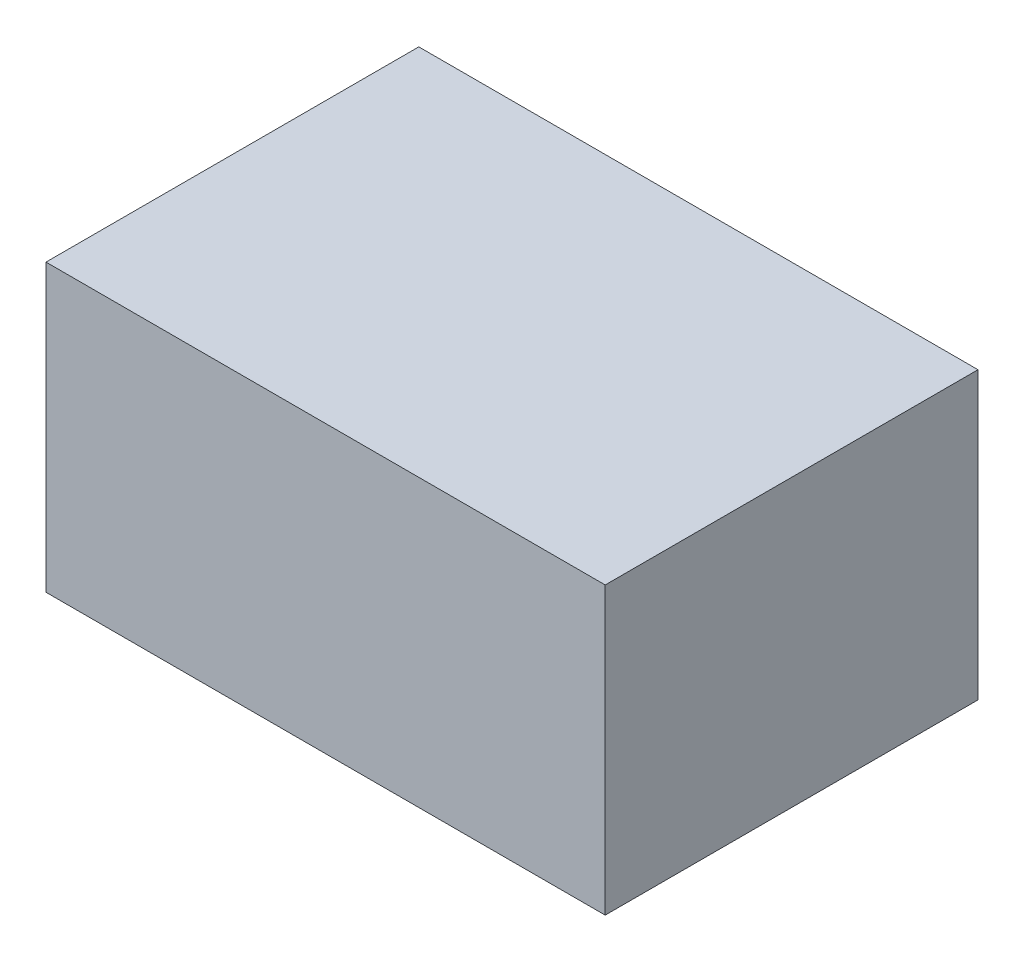
SolidWorks part; units mm, degrees
ref_plane "Front Plane" through (0, 0, 0) normal (0, 0, 1) x (1, 0, 0)
ref_plane "Top Plane" through (0, 0, 0) normal (0, 1, 0) x (1, 0, 0)
ref_plane "Right Plane" through (0, 0, 0) normal (1, 0, 0) x (0, 0, -1)
sketch "Sketch1" plane through (0, 0, 0) normal (0, 1, 0) x (1, 0, 0)
  line L1 (-210.7727, 130.4953) -> (-60.7727, 130.4953)
  line L2 (-210.7727, 130.4953) -> (-210.7727, 30.4953)
  line L3 (-210.7727, 30.4953) -> (-60.7727, 30.4953)
  line L4 (-60.7727, 130.4953) -> (-60.7727, 30.4953)
  line L5 (-210.7727, 130.4953) -> (-60.7727, 30.4953) construction
  line L6 (-210.7727, 30.4953) -> (-60.7727, 130.4953) construction
  point P0 (-135.7727, 80.4953)
  dimension "D1" = 150
  dimension "D2" = 100
extrude "Boss-Extrude1" add sketch "Sketch1" along normal blind 76.708
